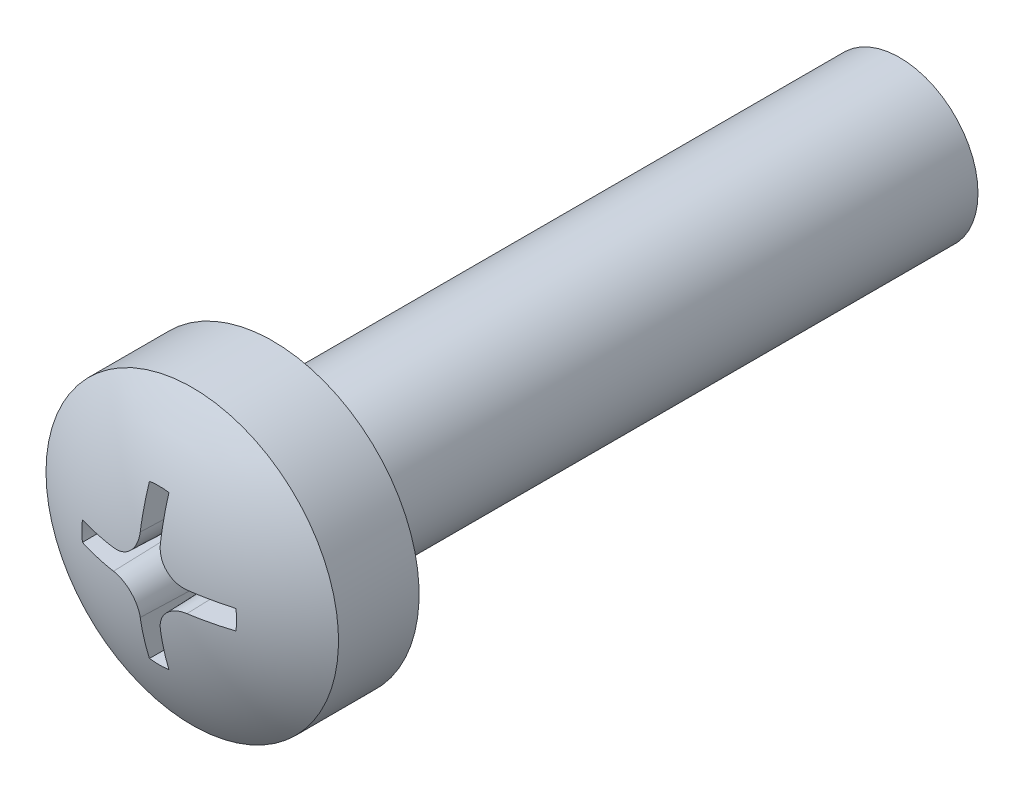
SolidWorks part; units mm, degrees
material "普通碳钢"
ref_plane "Plane1" through (0, 0, 0) normal (0, 0, 1) x (1, 0, 0)
ref_plane "Plane2" through (0, 0, 0) normal (0, 1, 0) x (1, 0, 0)
ref_plane "Plane3" through (0, 0, 0) normal (1, 0, 0) x (0, 0, -1)
sketch "Sketch1" plane through (0, 0, 0) normal (0, 0, 1) x (1, 0, 0)
  circle A0 centre (0, 0) radius 1.5
  dimension "D1" = 3
extrude "Base-Extrude" add sketch "Sketch1" along normal blind 12
sketch "Sketch6" plane through (0, 0, 0) normal (0, 1, 0) x (1, 0, 0)
  line L0 (0, 0.3936) -> (0, -34.4908) construction
  line L1 (0, -12) -> (0, 0) construction
  line L2 (0, -12) -> (2.8, -12)
  line L3 (2.8, -12) -> (2.8, -13.5425)
  line L4 (0, -14.4) -> (0, -12)
  line L5 (-1.5, -12) -> (1.5, -12) construction
  arc A0 (2.8, -13.5425) -> (0, -14.4) centre (0, -9.4) cw
  dimension "D1" = 2.4
  dimension "D9" = 5
  dimension "D8" = 2.8
revolve "Boss-Revolve2" add sketch "Sketch6" angle 360 about L0
ref_plane "Plane6" through (0, 0, 14.7) normal (0, 0, -1) x (-1, 0, 0)
sketch "Sketch7" plane through (0, 0, 14.7) normal (0, 0, -1) x (-1, 0, 0)
  line L0 (-7.1, 0) -> (5.9, 0) construction
  line L1 (0, 7.5) -> (0, -7) construction
  line L2 (0.205, 1.4859) -> (0.205, 0.7082)
  line L3 (0, 0) -> (4.9858, 4.9858) construction
  line L4 (1.4859, 0.205) -> (0.703, 0.2082)
  line L5 (1.4859, -0.205) -> (0.703, -0.2082)
  line L6 (0.205, -1.4859) -> (0.205, -0.7082)
  line L7 (-0.205, -1.4859) -> (-0.205, -0.7082)
  line L8 (-1.4859, -0.205) -> (-0.703, -0.2082)
  line L9 (-1.4859, 0.205) -> (-0.703, 0.2082)
  line L10 (-0.205, 1.4859) -> (-0.205, 0.7082)
  arc A0 (-0.205, 1.4859) -> (0.205, 1.4859) centre (0, 0) cw
  arc A1 (1.4859, -0.205) -> (1.4859, 0.205) centre (0, 0) ccw
  arc A2 (0.205, 0.7082) -> (0.703, 0.2082) centre (0.705, 0.7082) ccw
  arc A3 (-0.205, 0.7082) -> (-0.703, 0.2082) centre (-0.705, 0.7082) cw
  arc A4 (-0.205, -1.4859) -> (0.205, -1.4859) centre (0, 0) ccw
  arc A5 (-0.205, -0.7082) -> (-0.703, -0.2082) centre (-0.705, -0.7082) ccw
  arc A6 (-1.4859, -0.205) -> (-1.4859, 0.205) centre (0, 0) cw
  arc A7 (0.703, -0.2082) -> (0.205, -0.7082) centre (0.705, -0.7082) ccw
  dimension "D1" = 0.5
  dimension "D10" = 1.5
  dimension "D11" = 0.41
extrude "Cut-Extrude1" cut sketch "Sketch7" along normal blind 1.8 draft 2
